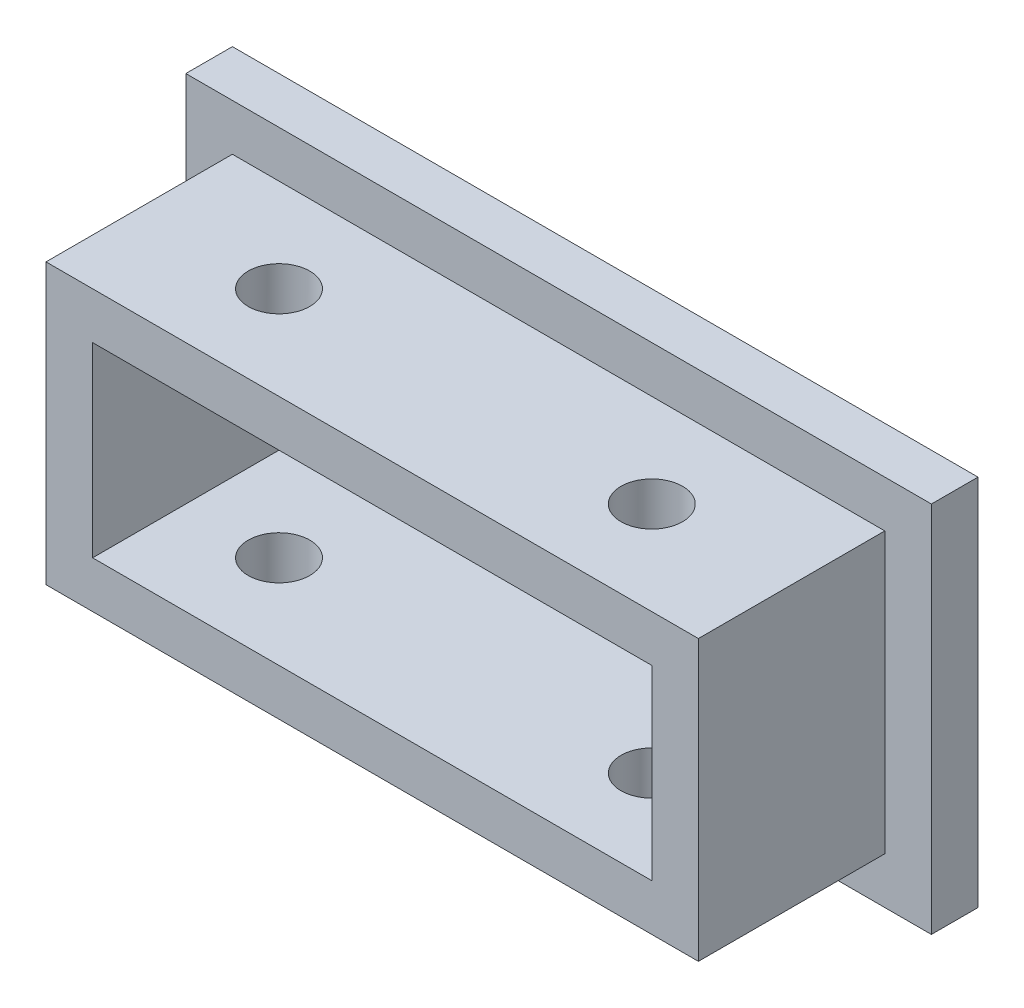
SolidWorks part; units mm, degrees
material "ABS"
ref_plane "Front Plane" through (0, 0, 0) normal (0, 0, 1) x (1, 0, 0)
ref_plane "Top Plane" through (0, 0, 0) normal (0, 1, 0) x (1, 0, 0)
ref_plane "Right Plane" through (0, 0, 0) normal (1, 0, 0) x (0, 0, -1)
sketch "Sketch1" plane through (0, 0, 0) normal (0, 0, 1) x (1, 0, 0)
  line L0 (14.8167, -6.35) -> (22.225, -9.525) construction
  line L1 (-22.225, 9.525) -> (22.225, 9.525)
  line L2 (-22.225, 9.525) -> (-22.225, -9.525)
  line L3 (-22.225, -9.525) -> (22.225, -9.525)
  line L4 (22.225, 9.525) -> (22.225, -9.525)
  line L5 (-22.225, 9.525) -> (-14.8167, 6.35) construction
  line L6 (-22.225, -9.525) -> (-14.8167, -6.35) construction
  line L7 (-19.05, 6.35) -> (19.05, 6.35)
  line L8 (-19.05, 6.35) -> (-19.05, -6.35)
  line L9 (-19.05, -6.35) -> (19.05, -6.35)
  line L10 (19.05, 6.35) -> (19.05, -6.35)
  line L11 (14.8167, 6.35) -> (22.225, 9.525) construction
  point P0 (0, 0)
  dimension "D1" = 44.45
  dimension "D2" = 19.05
  dimension "D3" = 3.175
  dimension "D4" = 3.175
  dimension "D5" = 3.175
  dimension "D6" = 3.175
extrude "Boss-Extrude1" add sketch "Sketch1" along normal blind 12.7
sketch "Sketch2" plane through (0, 9.525, 0) normal (0, 1, 0) x (1, 0, 0)
  line L0 (-22.225, -6.35) -> (-19.05, -6.35) construction
  line L1 (-22.225, -12.7) -> (-22.225, 0) construction
  line L2 (-19.05, -6.35) -> (-12.7, -6.35) construction
  line L3 (0, 0) -> (0, -12.7) construction
  line L4 (22.225, -12.7) -> (-22.225, -12.7) construction
  line L5 (22.225, -6.35) -> (19.05, -6.35) construction
  line L6 (19.05, -6.35) -> (12.7, -6.35) construction
  circle A0 centre (-12.7, -6.35) radius 2.0955
  circle A1 centre (12.7, -6.35) radius 2.0955
  dimension "D3" = 4.191
  dimension "D1" = 3.175
  dimension "D2" = 6.35
extrude "Cut-Extrude1" cut sketch "Sketch2" against normal up to surface (19.05 mm away) up to face at (0, -9.525, 6.35)
sketch "Sketch3" plane through (0, 0, 0) normal (0, 0, -1) x (-1, 0, 0)
  line L0 (-22.225, 9.525) -> (22.225, 9.525) construction
  line L1 (-25.4, 12.7) -> (25.4, 12.7)
  line L2 (-25.4, 12.7) -> (-25.4, -12.7)
  line L3 (-25.4, -12.7) -> (25.4, -12.7)
  line L4 (25.4, 12.7) -> (25.4, -12.7)
  line L5 (-25.4, 12.7) -> (25.4, -12.7) construction
  line L6 (-25.4, -12.7) -> (25.4, 12.7) construction
  line L8 (-22.225, -9.525) -> (-22.225, 9.525) construction
  line L9 (22.225, 9.525) -> (22.225, -9.525) construction
  point P0 (0, 0)
  dimension "D1" = 3.175
  dimension "D2" = 3.175
  dimension "D3" = 3.175
extrude "Boss-Extrude2" add sketch "Sketch3" along normal blind 3.175
